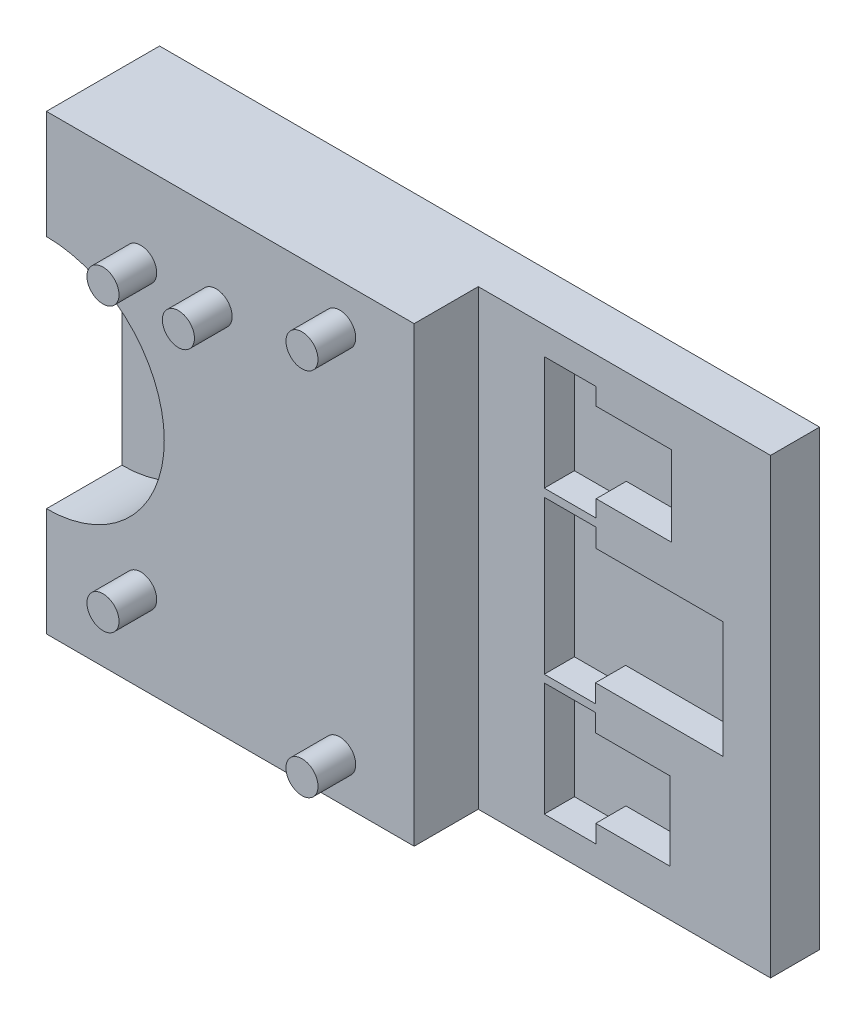
SolidWorks part; units mm, degrees
ref_plane "Front" through (0, 0, 0) normal (0, 0, 1) x (1, 0, 0)
ref_plane "Top" through (0, 0, 0) normal (0, 1, 0) x (1, 0, 0)
ref_plane "Right" through (0, 0, 0) normal (1, 0, 0) x (0, 0, -1)
sketch "Sketch1" plane through (0, 0, 0) normal (0, 0, 1) x (1, 0, 0)
  line L1 (0, 0) -> (44.45, 0)
  line L2 (0, 0) -> (0, 30.48)
  line L3 (0, 30.48) -> (44.45, 30.48)
  line L4 (44.45, 0) -> (44.45, 30.48)
  dimension "D1" = 30.48
  dimension "D2" = 44.45
extrude "Boss-Extrude1" add sketch "Sketch1" along normal blind 7.62
sketch "Sketch2" plane through (0, 0, 7.62) normal (0, 0, 1) x (1, 0, 0)
  line L0 (0, 15.24) -> (44.45, 15.24) construction
  line L1 (0, 30.48) -> (0, 0) construction
  line L2 (44.45, 0) -> (44.45, 30.48) construction
  line L3 (6.35, 0) -> (6.35, 30.48) construction
  line L4 (0, 0) -> (44.45, 0) construction
  line L5 (44.45, 30.48) -> (0, 30.48) construction
  line L6 (19.7514, 26.0985) -> (19.7514, 4.3815) construction
  line L7 (6.35, 24.765) -> (19.7514, 27.686) construction
  line L8 (7.9011, 25.1031) -> (18.2003, 27.3479) construction
  circle A0 centre (6.35, 24.765) radius 1.0795
  circle A1 centre (6.35, 5.715) radius 1.0795
  circle A2 centre (11.43, 24.765) radius 1.0795
  circle A3 centre (19.7514, 27.686) radius 1.5875 construction
  circle A4 centre (19.7514, 2.794) radius 1.5875 construction
  circle A5 centre (6.35, 24.765) radius 1.5875 construction
  circle A6 centre (19.7514, 27.686) radius 1.0795
  circle A7 centre (19.7514, 2.794) radius 1.0795
  dimension "D4" = 2.159
  dimension "D5" = 2.159
  dimension "D6" = 2.159
  dimension "D11" = 3.175
  dimension "D12" = 3.175
  dimension "D10" = 3.175
  dimension "D14" = 2.159
  dimension "D15" = 2.159
  dimension "D1" = 6.35
  dimension "D2" = 19.05
  dimension "D3" = 9.525
  dimension "D7" = 5.08
  dimension "D8" = 21.717
  dimension "D9" = 10.8585
  dimension "D13" = 10.541
extrude "Boss-Extrude2" add sketch "Sketch2" along normal blind 2.54
sketch "Sketch3" plane through (0, 0, 7.62) normal (0, 0, 1) x (1, 0, 0)
  line L0 (0, 30.48) -> (0, 0) construction
  circle A0 centre (0, 15.24) radius 7.9375
  dimension "D1" = 15.875
extrude "Cut-Extrude1" cut sketch "Sketch3" against normal offset from surface (5.08 mm away) 2.54 up to face at (22.225, 15.24, 0)
sketch "Sketch4" plane through (0, 0, 7.62) normal (0, 0, 1) x (1, 0, 0)
  line L0 (0, 0) -> (44.45, 0) construction
  line L1 (44.45, 30.48) -> (29.21, 30.48)
  line L2 (44.45, 30.48) -> (44.45, 0)
  line L3 (44.45, 0) -> (29.21, 0)
  line L4 (29.21, 30.48) -> (29.21, 0)
  line L5 (0, 7.3025) -> (0, 0) construction
  dimension "D1" = 29.21
extrude "Cut-Extrude2" cut sketch "Sketch4" against normal offset from surface (6.35 mm away) 6.35 up to face at (18.6719, 2.794, 7.62)
sketch "Sketch5" plane through (0, 0, 7.62) normal (0, 0, 1) x (1, 0, 0)
  line L0 (29.21, 30.48) -> (0, 30.48) construction
  line L1 (29.21, 0) -> (24.765, 0)
  line L2 (29.21, 0) -> (29.21, 30.48)
  line L3 (29.21, 30.48) -> (24.765, 30.48)
  line L4 (24.765, 0) -> (24.765, 30.48)
  dimension "D1" = 4.445
extrude "Cut-Extrude3" cut sketch "Sketch5" against normal offset from surface (4.318 mm away) 2.032 up to face at (36.83, 15.24, 1.27)
sketch "Sketch6" plane through (0, 0, 1.27) normal (0, 0, 1) x (1, 0, 0)
  line L0 (29.21, 0) -> (29.21, 1.9378)
  line L1 (29.21, 0) -> (29.21, 30.48) construction
  line L2 (29.21, 1.9378) -> (32.6788, 1.9378)
  line L3 (32.6788, 1.9378) -> (32.6788, 3.1335)
  line L4 (32.6788, 3.1335) -> (37.6869, 3.1335)
  line L5 (37.6869, 3.1335) -> (37.6869, 8.4021)
  line L6 (37.6869, 8.4021) -> (32.6583, 8.4021)
  line L8 (32.6583, 8.4021) -> (32.6583, 9.5906)
  line L9 (32.6583, 9.5906) -> (29.21, 9.5906)
  line L10 (29.21, 9.5906) -> (29.21, 10.0971)
  line L11 (29.21, 10.0971) -> (32.6583, 10.0971)
  line L12 (32.6583, 10.0971) -> (32.6583, 11.3222)
  line L13 (32.6583, 11.3222) -> (41.2375, 11.3222)
  line L14 (41.2375, 11.3222) -> (41.2375, 19.1773)
  line L15 (41.2375, 19.1773) -> (32.7037, 19.1773)
  line L16 (32.7037, 19.1773) -> (32.7037, 20.4175)
  line L17 (32.7037, 20.4175) -> (29.21, 20.4175)
  line L18 (29.21, 20.4175) -> (29.21, 20.9493)
  line L19 (29.21, 20.9493) -> (32.7037, 20.9493)
  line L20 (32.7037, 20.9493) -> (32.7037, 22.0793)
  line L21 (32.7037, 22.0793) -> (37.7714, 22.0793)
  line L22 (37.7714, 22.0793) -> (37.7714, 27.4733)
  line L23 (37.7714, 27.4733) -> (32.7026, 27.4733)
  line L24 (32.7026, 27.4733) -> (32.7026, 28.6226)
  line L25 (32.7026, 28.6226) -> (29.21, 28.6226)
  line L26 (29.21, 28.6226) -> (29.21, 30.48)
  line L27 (29.21, 30.48) -> (44.45, 30.48)
  line L28 (44.45, 30.48) -> (44.45, 0)
  line L29 (44.45, 0) -> (29.21, 0)
extrude "Boss-Extrude3" add sketch "Sketch6" along normal up to surface (2.032 mm away) up to face at (26.9875, 15.24, 3.302)
equation "\"D3@Sketch2\"=\"D2@Sketch2\"/2"
equation "\"D9@Sketch2\"=\"D8@Sketch2\"/2"
